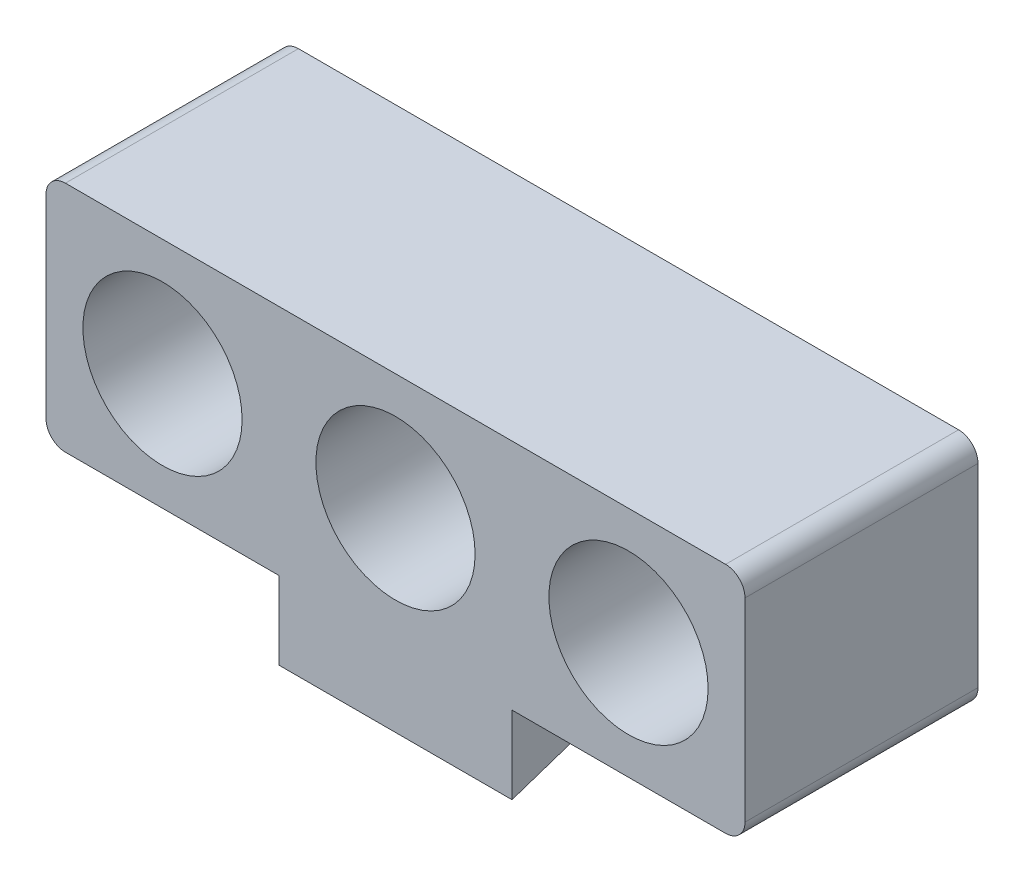
SolidWorks part; units mm, degrees
material "Custom Plastic"
ref_plane "Front Plane" through (0, 0, 0) normal (0, 0, 1) x (1, 0, 0)
ref_plane "Top Plane" through (0, 0, 0) normal (0, 1, 0) x (1, 0, 0)
ref_plane "Right Plane" through (0, 0, 0) normal (1, 0, 0) x (0, 0, -1)
sketch "Sketch1" plane through (0, 0, 0) normal (0, 0, 1) x (1, 0, 0)
  line L1 (18, -6) -> (-18, -6)
  line L2 (18, -6) -> (18, 6)
  line L3 (18, 6) -> (-18, 6)
  line L4 (-18, -6) -> (-18, 6)
  line L5 (18, -6) -> (-18, 6) construction
  line L6 (18, 6) -> (-18, -6) construction
  point P0 (0, 0)
  dimension "D1" = 36
  dimension "D2" = 12
extrude "Boss-Extrude1" add sketch "Sketch1" along normal blind 12
hole_wizard "Ø3.0mm Dowel Hole1" positions "Sketch2" profile "Sketch3" hole size "Ø3.0" standard "ANSI Metric"
sketch "Sketch2" plane through (0, 0, 12) normal (0, 0, 1) x (1, 0, 0)
  line L0 (-18, 6) -> (-18, -6) construction
  line L1 (18, -6) -> (18, 6) construction
  point P0 (-12, 0)
  point P2 (12, 0)
  point P11 (0, 0)
  dimension "D1" = 6
  dimension "D2" = 6
sketch "Sketch3" plane through (-12, 0, 12) normal (1, 0, 0) x (0, -1, 0)
  line L0 (0, 0) -> (0, 11.999)
  line L1 (0, 11.999) -> (4.1, 11.999)
  line L2 (4.1, 11.999) -> (4.1, 0)
  line L5 (4.1, 0) -> (0, 0)
  line L10 (0, 11.999) -> (-4.1, 11.999) construction
  line L11 (0, -6.35) -> (0, 107.95) construction
  dimension "Hole Dia." = 8.2
  dimension "Hole Depth" = 11.999
  dimension "Drill Angle" = 180
sketch "Sketch4" plane through (0, 0, 0) normal (-1, 0, 0) x (0, 0, 1)
  line L0 (12, -6) -> (12, -10)
  line L1 (12, -10) -> (0, -6)
  line L2 (12, -6) -> (0, -6) construction
  line L3 (12, -6) -> (0, -6)
  dimension "D1" = 4
extrude "Boss-Extrude2" add sketch "Sketch4" along normal mid plane 12
sketch "Sketch5" plane through (-6, 0, 0) normal (-1, 0, 0) x (0, 0, 1)
  line L0 (12, -10) -> (12, -6)
  line L1 (12, -10) -> (12, -6) construction
  line L3 (10.7332, -8) -> (10.7332, -6)
  line L4 (12, -6) -> (0, -6) construction
  line L5 (10.7332, -6) -> (12, -6)
  arc A0 (12, -10) -> (10.7332, -8) centre (-6, -20) ccw
  dimension "D1" = 6
  dimension "D2" = 14
  dimension "D3" = 2
fillet "Fillet2" radius 1 4 edges at (18, -6, 6) (18, 6, 6) (-18, -6, 6) (-18, 6, 6)
